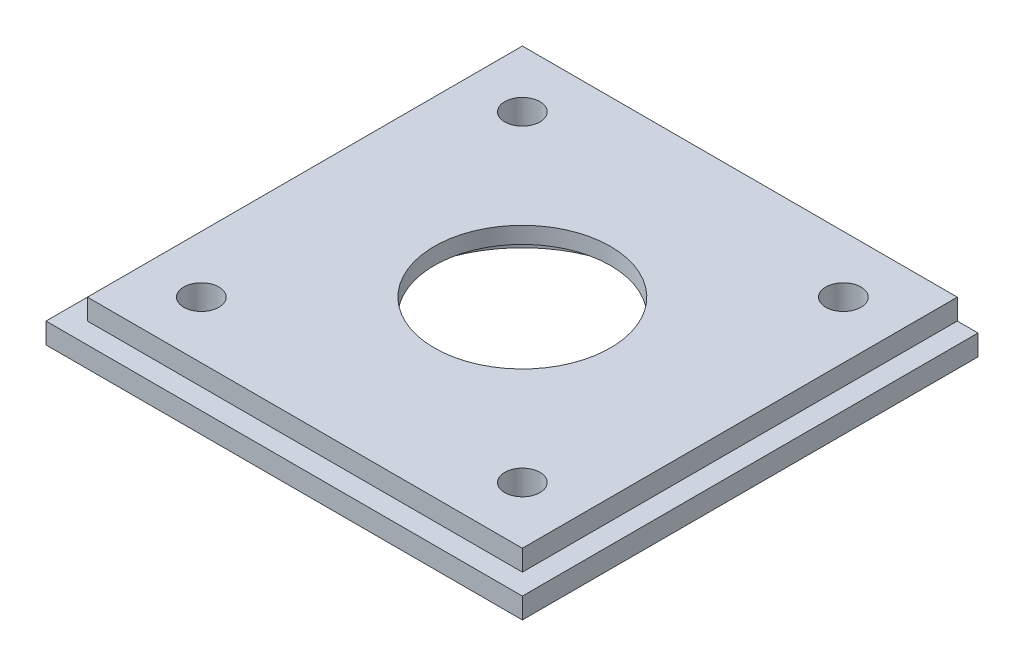
SolidWorks part; units mm, degrees
ref_plane "Ebene vorne" through (0, 0, 0) normal (0, 0, 1) x (1, 0, 0)
ref_plane "Ebene oben" through (0, 0, 0) normal (0, 1, 0) x (1, 0, 0)
ref_plane "Ebene rechts" through (0, 0, 0) normal (1, 0, 0) x (0, 0, -1)
sketch "Skizze1" plane through (0, 0, 0) normal (0, 1, 0) x (1, 0, 0)
  line L1 (-21, -21) -> (21, -21)
  line L2 (-21, -21) -> (-21, 21)
  line L3 (-21, 21) -> (21, 21)
  line L4 (21, -21) -> (21, 21)
  line L5 (-21, -21) -> (21, 21) construction
  line L6 (-21, 21) -> (21, -21) construction
  circle A0 centre (-15.5, 15.5) radius 1.7
  circle A1 centre (15.5, 15.5) radius 1.7
  circle A2 centre (-15.5, -15.5) radius 1.7
  circle A3 centre (15.5, -15.5) radius 1.7
  circle A4 centre (0, 0) radius 8.5
  point P4 (0, 0)
  dimension "D2" = 3.4
  dimension "D3" = 31
  dimension "D4" = 17
  dimension "D1" = 42
extrude "Aufsatz-Linear austragen1" add sketch "Skizze1" along normal blind 4
sketch "Skizze2" plane through (0, 0, 0) normal (0, -1, 0) x (1, 0, 0)
  circle A0 centre (0, 0) radius 11.5
  dimension "D1" = 23
extrude "Schnitt-Linear austragen1" cut sketch "Skizze2" against normal blind 2.4
sketch "Skizze4" plane through (0, 0, 0) normal (0, -1, 0) x (1, 0, 0)
  line L0 (-21, -21) -> (-21, 21)
  line L1 (-21, 21) -> (21, 21)
  line L2 (21, 21) -> (21, -21)
  line L3 (21, -21) -> (23, -21)
  line L4 (23, -21) -> (23, 23)
  line L5 (23, 23) -> (-23, 23)
  line L6 (-23, 23) -> (-23, -21)
  line L7 (-23, -21) -> (-21, -21)
  dimension "D1" = 2
  dimension "D2" = 2
  dimension "D3" = 2
extrude "Aufsatz-Linear austragen2" add sketch "Skizze4" against normal blind 2
equation "\"D2@Skizze4\"=\"D1@Skizze4\""
equation "\"D3@Skizze4\"=\"D1@Skizze4\""
